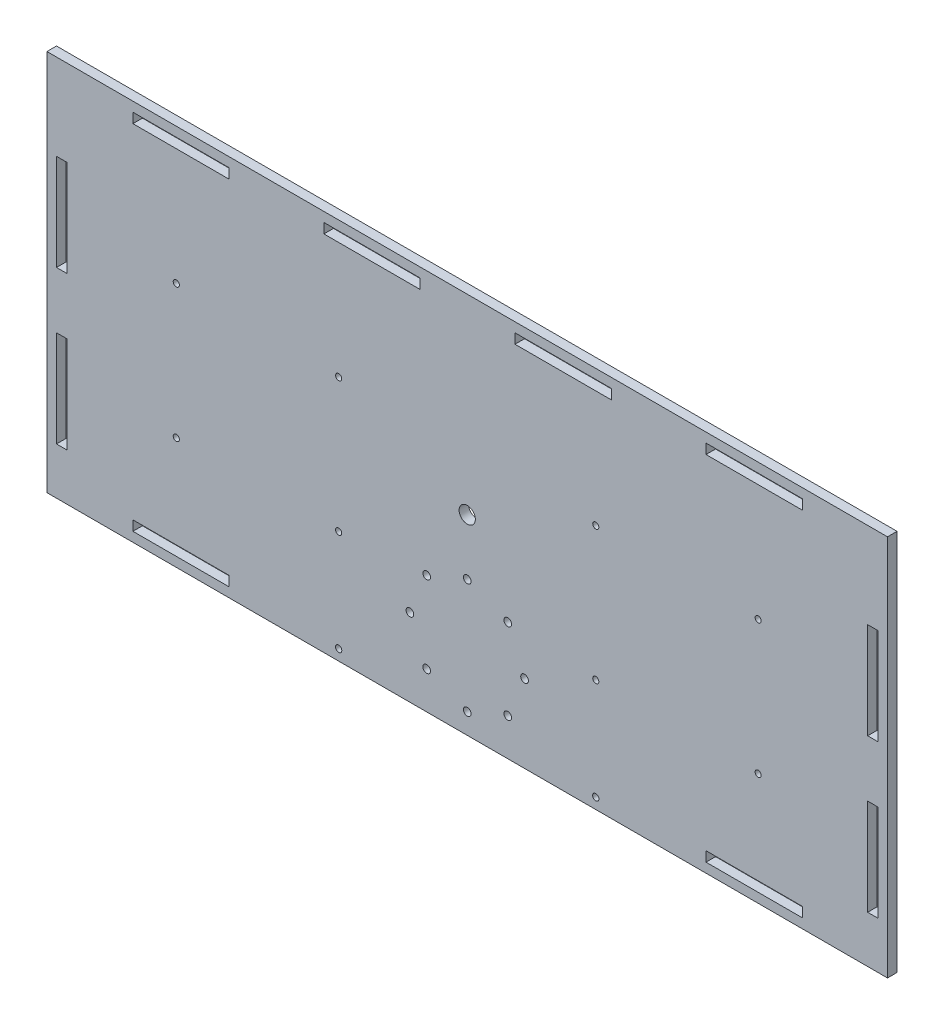
SolidWorks part; units mm, degrees
material "Balsa"
ref_plane "Plan de face" through (0, 0, 0) normal (0, 0, 1) x (1, 0, 0)
ref_plane "Plan de dessus" through (0, 0, 0) normal (0, 1, 0) x (1, 0, 0)
ref_plane "Plan de droite" through (0, 0, 0) normal (1, 0, 0) x (0, 0, -1)
sketch "Esquisse1" plane through (0, 0, 0) normal (0, 0, 1) x (1, 0, 0)
  line L0 (-220, 100) -> (-0.1458, 100)
  line L1 (220, -100) -> (-220, -100)
  line L2 (220, -100) -> (220, 100)
  line L4 (-220, -100) -> (-220, 100)
  line L5 (220, -100) -> (-220, 100) construction
  line L6 (220, 100) -> (-220, -100) construction
  line L7 (220, 100) -> (9.8542, 100)
  line L10 (-0.1458, 100) -> (9.8542, 100)
  line L19 (0, 0) -> (0, -146.4766) construction
  line L28 (-75, 95) -> (-75, 89.8)
  line L29 (-175, 95) -> (-124.6, 95)
  line L30 (-175, 95) -> (-175, 89.8)
  line L31 (-175, 89.8) -> (-124.6, 89.8)
  line L32 (-124.6, 95) -> (-124.6, 89.8)
  line L33 (-75, 95) -> (-24.6, 95)
  line L34 (-24.6, 95) -> (-24.6, 89.8)
  line L35 (-75, 89.8) -> (-24.6, 89.8)
  line L36 (25, 95) -> (25, 89.8)
  line L37 (25, 95) -> (75.4, 95)
  line L38 (75.4, 95) -> (75.4, 89.8)
  line L39 (25, 89.8) -> (75.4, 89.8)
  line L40 (125, 95) -> (125, 89.8)
  line L41 (125, 95) -> (175.4, 95)
  line L42 (175.4, 95) -> (175.4, 89.8)
  line L43 (125, 89.8) -> (175.4, 89.8)
  line L44 (-215, -25) -> (-215, -75.4)
  line L45 (-215, 55) -> (-209.6, 55)
  line L46 (-215, 55) -> (-215, 4.6)
  line L47 (-215, 4.6) -> (-209.6, 4.6)
  line L48 (-209.6, 55) -> (-209.6, 4.6)
  line L49 (-215, -25) -> (-209.6, -25)
  line L50 (-209.6, -25) -> (-209.6, -75.4)
  line L51 (-215, -75.4) -> (-209.6, -75.4)
  line L52 (215, -25) -> (209.6, -25)
  line L53 (209.6, -25) -> (209.6, -75.4)
  line L54 (215, -75.4) -> (209.6, -75.4)
  line L55 (215, -25) -> (215, -75.4)
  line L56 (215, 4.6) -> (209.6, 4.6)
  line L57 (209.6, 55) -> (209.6, 4.6)
  line L58 (215, 55) -> (209.6, 55)
  line L59 (215, 55) -> (215, 4.6)
  line L60 (220, 0) -> (-220, 0) construction
  line L65 (175.4, -95) -> (175.4, -89.8)
  line L66 (125, -89.8) -> (175.4, -89.8)
  line L67 (125, -95) -> (175.4, -95)
  line L68 (125, -95) -> (125, -89.8)
  line L73 (-175, -95) -> (-175, -89.8)
  line L74 (-124.6, -95) -> (-124.6, -89.8)
  line L75 (-175, -89.8) -> (-124.6, -89.8)
  line L76 (-175, -95) -> (-124.6, -95)
  line L77 (-47.7616, -59.269) -> (47.7616, -59.269) construction
  line L78 (-47.7616, -100) -> (-47.7616, -18.538) construction
  line L79 (47.7616, -18.538) -> (47.7616, -100) construction
  circle A2 centre (-67.3, -94.377) radius 1.65
  circle A3 centre (67.3, -94.377) radius 1.65
  circle A5 centre (152.3, -41.2491) radius 1.6031
  circle A6 centre (152.3, 28.7509) radius 1.605
  circle A7 centre (67.3, 28.7509) radius 1.605
  circle A8 centre (67.3, -41.2491) radius 1.605
  circle A9 centre (-67.3, 28.7509) radius 1.605
  circle A10 centre (-67.3, -41.2491) radius 1.605
  circle A11 centre (-152.3, 28.7509) radius 1.605
  circle A12 centre (-152.3, -41.2491) radius 1.605
  circle A13 centre (0, 0) radius 4.25
  circle A14 centre (0, -29.269) radius 2
  circle A15 centre (21.2132, -38.0558) radius 2
  circle A16 centre (30, -59.269) radius 2
  circle A17 centre (21.2132, -80.4822) radius 2
  circle A18 centre (0, -89.269) radius 2
  circle A19 centre (-21.2132, -80.4822) radius 2
  circle A20 centre (-30, -59.269) radius 2
  circle A21 centre (-21.2132, -38.0558) radius 2
  point P0 (0, 0)
  point P77 (0, -59.269)
  point P98 (0, -59.269)
  dimension "D8" = 4
  dimension "D14" = 3.21
  dimension "D15" = 3.2063
  dimension "D16" = 3.21
  dimension "D17" = 3.21
  dimension "D18" = 3.21
  dimension "D19" = 3.21
  dimension "D20" = 3.21
  dimension "D21" = 3.21
  dimension "D22" = 8.5
  dimension "D23" = 30
  dimension "D1" = 5
  dimension "D2" = 440
  dimension "D3" = 5.2
  dimension "D4" = 50.4
  dimension "D5" = 45
  dimension "D6" = 4
  dimension "D7" = 50.4
  dimension "D10" = 45
  dimension "D11" = 5.4
  dimension "D12" = 5
  dimension "D13" = 2
  dimension "D9" = 8
extrude "Boss.-Extru.1" add sketch "Esquisse1" along normal blind 5
